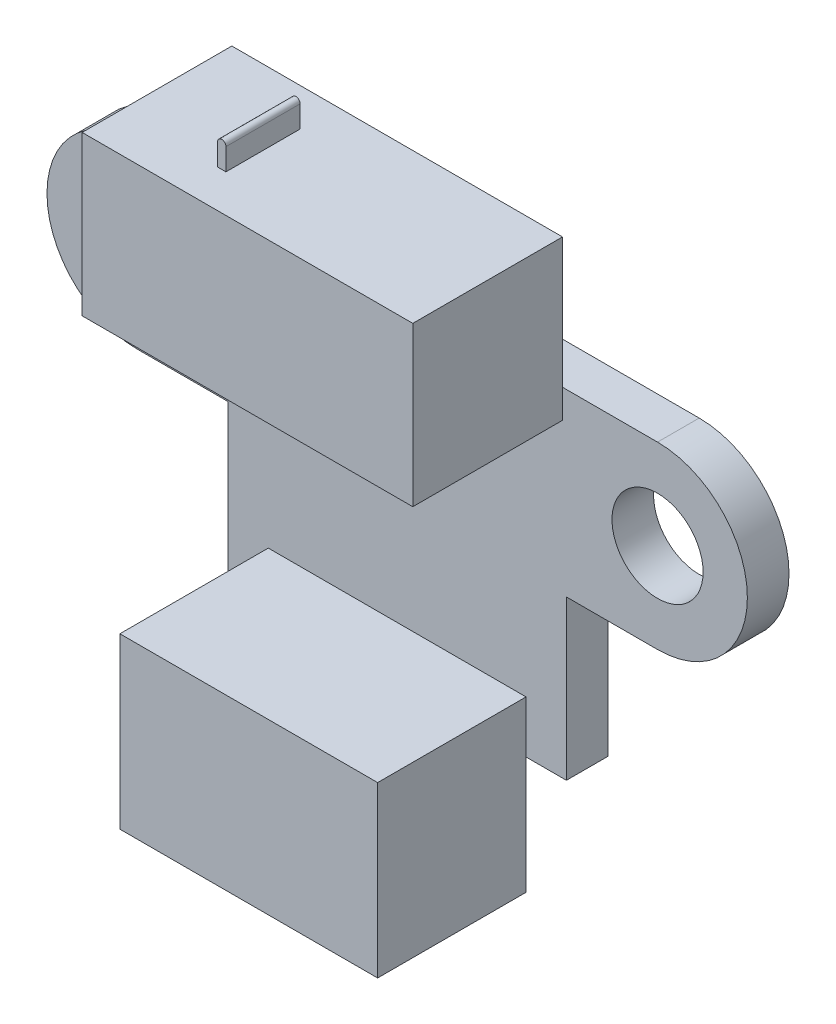
SolidWorks part; units mm, degrees
ref_plane "Front Plane" through (0, 0, 0) normal (0, 0, 1) x (1, 0, 0)
ref_plane "Top Plane" through (0, 0, 0) normal (0, 1, 0) x (1, 0, 0)
ref_plane "Right Plane" through (0, 0, 0) normal (1, 0, 0) x (0, 0, -1)
sketch "Sketch1" plane through (0, 0, 0) normal (0, 0, 1) x (1, 0, 0)
  line L0 (0, -6.9) -> (0, -13)
  line L1 (0, -13) -> (13, -13)
  line L2 (13, -13) -> (13, -6.9)
  line L3 (13, 0) -> (0, 0)
  line L4 (13, 0) -> (16.5, 0)
  line L5 (0, 0) -> (-3.5, 0)
  line L6 (16.5, -6.9) -> (13, -6.9)
  line L8 (-3.5, -6.9) -> (0, -6.9)
  arc A0 (16.5, 0) -> (16.5, -6.9) centre (16.5, -3.45) cw
  arc A1 (-3.5, 0) -> (-3.5, -6.9) centre (-3.5, -3.45) ccw
  dimension "D4" = 6.9
  dimension "D1" = 13
  dimension "D2" = 13
  dimension "D3" = 3.5
  dimension "D5" = 3.5
extrude "Boss-Extrude1" add sketch "Sketch1" along normal blind 1.6
sketch "Sketch2" plane through (0, 0, 1.6) normal (0, 0, 1) x (1, 0, 0)
  line L0 (1.55, -11) -> (1.55, -17.5)
  line L1 (1.55, -17.5) -> (11.45, -17.5)
  line L2 (11.45, -17.5) -> (11.45, -11)
  line L3 (11.45, -11) -> (1.55, -11)
  line L4 (0, -6.9) -> (0, -13) construction
  line L7 (0, -13) -> (13, -13) construction
  dimension "D1" = 9.9
  dimension "D2" = 1.55
  dimension "D3" = 2
  dimension "D4" = 4.5
extrude "Boss-Extrude2" add sketch "Sketch2" along normal blind 5.7
sketch "Sketch3" plane through (0, -17.5, 0) normal (0, -1, 0) x (1, 0, 0)
  line L0 (2.3, 6.55) -> (10.7, 6.55)
  line L1 (10.7, 6.55) -> (10.7, 2.35)
  line L2 (10.7, 2.35) -> (2.3, 2.35)
  line L3 (2.3, 2.35) -> (2.3, 6.55)
  line L4 (1.55, 7.3) -> (11.45, 7.3) construction
  line L5 (1.55, 1.6) -> (11.45, 1.6) construction
  line L6 (11.45, 7.3) -> (11.45, 1.6) construction
  line L7 (1.55, 7.3) -> (1.55, 1.6) construction
  dimension "D1" = 0.75
  dimension "D2" = 0.75
  dimension "D3" = 0.75
  dimension "D4" = 0.75
extrude "Cut-Extrude1" cut sketch "Sketch3" against normal blind 5.75
sketch "Sketch4" plane through (0, 0, 1.6) normal (0, 0, 1) x (1, 0, 0)
  circle A0 centre (-3.5, -3.45) radius 1.75
  circle A1 centre (16.5, -3.45) radius 1.75
  point P6 (-5.25, -3.45)
  point P7 (18.25, -3.45)
  dimension "D1" = 3.5
  dimension "D2" = 3.5
extrude "Cut-Extrude2" cut sketch "Sketch4" against normal blind 5.75
sketch "Sketch5" plane through (0, 0, 1.6) normal (0, 0, 1) x (1, 0, 0)
  line L0 (0.15, 5) -> (0.15, -1.1)
  line L1 (0.15, -1.1) -> (12.85, -1.1)
  line L2 (12.85, -1.1) -> (12.85, 5)
  line L3 (12.85, 5) -> (0.15, 5)
  line L4 (16.5, 0) -> (-3.5, 0) construction
  point P6 (6.5, 0)
  point P7 (6.5, -1.1)
  dimension "D1" = 1.1
  dimension "D2" = 6.1
  dimension "D3" = 12.7
extrude "Boss-Extrude3" add sketch "Sketch5" along normal blind 5.75
sketch "Sketch7" plane through (0, 0, 7.35) normal (0, 0, 1) x (1, 0, 0)
  line L0 (3.9, 5) -> (3.9, 5.8385)
  line L1 (12.85, 5) -> (0.15, 5) construction
  line L3 (4.223, 5.8385) -> (4.223, 5)
  line L4 (4.223, 5) -> (3.9, 5)
  arc A0 (3.9, 5.8385) -> (4.223, 5.8385) centre (4.0615, 5.8385) cw
  point P9 (4.0615, 6)
  dimension "D1" = 1
  dimension "D2" = 3.75
extrude "Boss-Extrude4" add sketch "Sketch7" against normal blind 5.75
sketch "Sketch8" plane through (12.85, 0, 0) normal (1, 0, 0) x (0, 0, -1)
  line L0 (-7.35, 5) -> (-1.6, 5) construction
  line L1 (-7.35, 5) -> (-5.9, 5)
  line L2 (-5.9, 5) -> (-5.9, 6.3)
  line L3 (-5.9, 6.3) -> (-7.35, 6.3)
  line L4 (-7.35, 6.3) -> (-7.35, 5)
  line L5 (-1.6, 5) -> (-1.6, 6.3)
  line L6 (-1.6, 6.3) -> (-3.05, 6.3)
  line L7 (-3.05, 6.3) -> (-3.05, 5)
  line L8 (-1.6, 5) -> (-7.35, 5) construction
  line L9 (-3.05, 5) -> (-1.6, 5)
  dimension "D1" = 1.45
  dimension "D2" = 1.45
extrude "Cut-Extrude3" cut sketch "Sketch8" against normal blind 10
